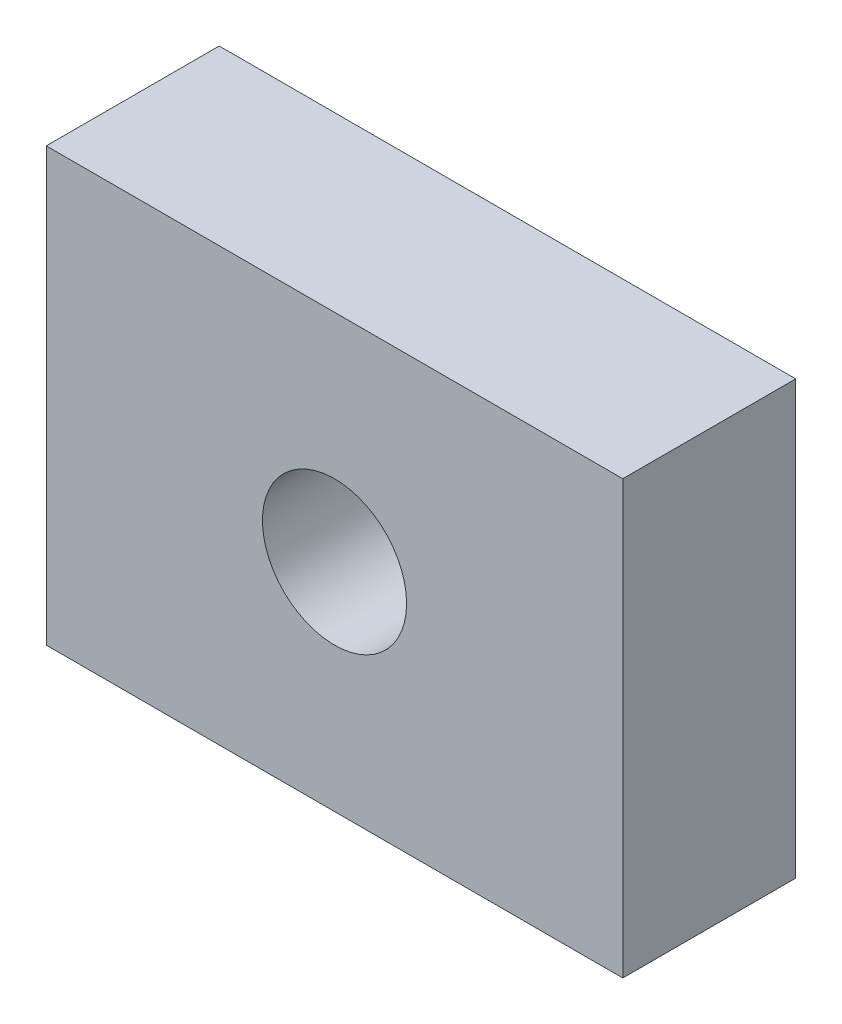
SolidWorks part; units mm, degrees
ref_plane "前视基准面" through (0, 0, 0) normal (0, 0, 1) x (1, 0, 0)
ref_plane "上视基准面" through (0, 0, 0) normal (0, 1, 0) x (1, 0, 0)
ref_plane "右视基准面" through (0, 0, 0) normal (1, 0, 0) x (0, 0, -1)
other "Configuration Table"
sketch "草图1" plane through (0, 0, 0) normal (0, 0, 1) x (1, 0, 0)
  line L0 (-20, -15) -> (20, -15)
  line L1 (20, -15) -> (20, 15)
  line L2 (20, 15) -> (-20, 15)
  line L3 (-20, 15) -> (-20, -15)
extrude "凸台-拉伸1" add sketch "草图1" along normal blind 12
sketch "草图2" plane through (0, 0, 12) normal (0, 0, 1) x (1, 0, 0)
  circle A0 centre (0, 0) radius 5
extrude "切除-拉伸1" cut sketch "草图2" against normal through all
